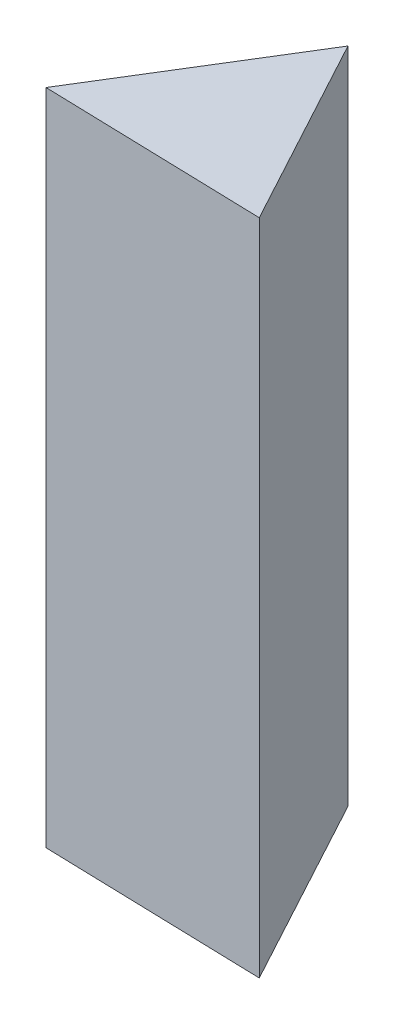
SolidWorks part; units mm, degrees
ref_plane "前视基准面" through (0, 0, 0) normal (0, 0, 1) x (1, 0, 0)
ref_plane "上视基准面" through (0, 0, 0) normal (0, 1, 0) x (1, 0, 0)
ref_plane "右视基准面" through (0, 0, 0) normal (1, 0, 0) x (0, 0, -1)
sketch "草图1" plane through (0, 0, 0) normal (0, 1, 0) x (1, 0, 0)
  line L1 (12.2926, -7.5647) -> (0.4049, 14.4281)
  line L2 (0.4049, 14.4281) -> (-12.6975, -6.8634)
  line L3 (-12.6975, -6.8634) -> (12.2926, -7.5647)
  circle A0 centre (0, 0) radius 7.2169 construction
extrude "凸台-拉伸1" add sketch "草图1" along normal blind 75
